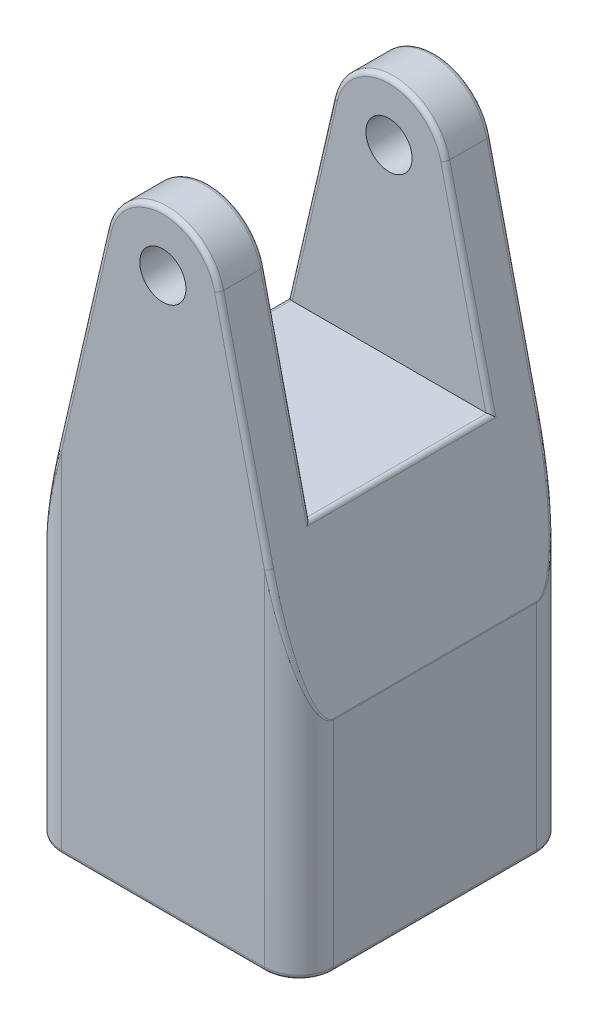
SolidWorks part; units mm, degrees
ref_plane "前视基准面" through (0, 0, 0) normal (0, 0, 1) x (1, 0, 0)
ref_plane "上视基准面" through (0, 0, 0) normal (0, 1, 0) x (1, 0, 0)
ref_plane "右视基准面" through (0, 0, 0) normal (1, 0, 0) x (0, 0, -1)
sketch "草图1" plane through (0, 0, 0) normal (0, 1, 0) x (1, 0, 0)
  line L0 (5.9, 5.9) -> (5.9, -5.9)
  line L1 (5.9, 5.9) -> (-5.9, 5.9)
  line L2 (5.9, -5.9) -> (-5.9, -5.9)
  line L3 (-5.9, 5.9) -> (-5.9, -5.9)
  line L4 (5.9, 5.9) -> (-5.9, -5.9) construction
  line L5 (5.9, -5.9) -> (-5.9, 5.9) construction
  point P1 (0, 0)
  dimension "D1" = 11.8
  dimension "D2" = 11.8
extrude "凸台-拉伸1" add sketch "草图1" along normal blind 9.5
sketch "草图2" plane through (0, 0, 5.9) normal (0, 0, 1) x (1, 0, 0)
  line L0 (-5.9, 9.5) -> (5.9, 9.5)
  line L1 (5.9, 9.5) -> (4.4, 16)
  line L2 (4.4, 16) -> (-4.4, 16)
  line L3 (-4.4, 16) -> (-5.9, 9.5)
  line L4 (5.9, 9.5) -> (5.9, 0) construction
  line L5 (-5.9, 9.5) -> (-5.9, 0) construction
  dimension "D1" = 6.5
  dimension "D2" = 1.5
  dimension "D3" = 1.5
extrude "凸台-拉伸2" add sketch "草图2" against normal blind 11.8
sketch "草图3" plane through (0, 0, 5.9) normal (0, 0, 1) x (1, 0, 0)
  line L0 (-4.4, 16) -> (4.4, 16)
  line L1 (4.4, 16) -> (2.436, 24.5108)
  line L2 (-4.4, 16) -> (-2.436, 24.5108)
  line L3 (-4.4, 16) -> (-5.9, 9.5) construction
  line L4 (5.9, 9.5) -> (4.4, 16) construction
  arc A0 (2.436, 24.5108) -> (-2.436, 24.5108) centre (0, 23.9486) ccw
  dimension "D3" = 5
  dimension "D1" = 180
  dimension "D2" = 180
extrude "凸台-拉伸3" add sketch "草图3" against normal blind 2
sketch "草图4" plane through (0, 0, 5.9) normal (0, 0, 1) x (1, 0, 0)
  circle A0 centre (0, 23.9486) radius 1
  dimension "D1" = 2
extrude "切除-拉伸1" cut sketch "草图4" against normal up to next
mirror "镜向1" about plane through (0, 0, 0) normal (0, 0, 1) of "切除-拉伸1", "凸台-拉伸3"
sketch "草图5" plane through (0, 0, 0) normal (0, 0, 1) x (1, 0, 0)
  line L0 (0, 0) -> (0, 14)
  line L1 (0, 14) -> (3, 14)
  line L2 (3, 14) -> (4, 9.5)
  line L3 (4, 9.5) -> (4, 0)
  line L4 (-5.9, 0) -> (5.9, 0) construction
  line L5 (4, 0) -> (0, 0)
  dimension "D1" = 4
  dimension "D2" = 9.5
  dimension "D3" = 14
  dimension "D4" = 3
revolve "切除-旋转1" cut sketch "草图5" angle 360 about L0
fillet "圆角1" radius 1.5 4 edges at (5.9, 4.75, -5.9) (5.9, 4.75, 5.9) (-5.9, 4.75, -5.9) (-5.9, 4.75, 5.9)
fillet "圆角2" radius 0.2 28 edges at (3.418, 20.2554, 5.9) (5.4607, 11.4038, 5.4607) (5.9, 9.5, 0) (5.4607, 11.4038, -5.4607) (3.418, 20.2554, -5.9) (0, 26.4486, -5.9) (0, 26.4486, -3.9) (-3.418, 20.2554, -5.9) (-5.4607, 11.4038, -5.4607) (-5.9, 9.5, 0) (-5.4607, 11.4038, 5.4607) (-3.418, 20.2554, 5.9) (0, 0, 5.9) (5.4607, 0, 5.4607) (5.9, 0, 0) (5.4607, 0, -5.4607) (0, 0, -5.9) (-5.4607, 0, -5.4607) (-5.9, 0, 0) (0, 26.4486, 5.9) (0, 26.4486, 3.9) (-5.4607, 0, 5.4607) (-3.418, 20.2554, -3.9) (3.418, 20.2554, -3.9)
